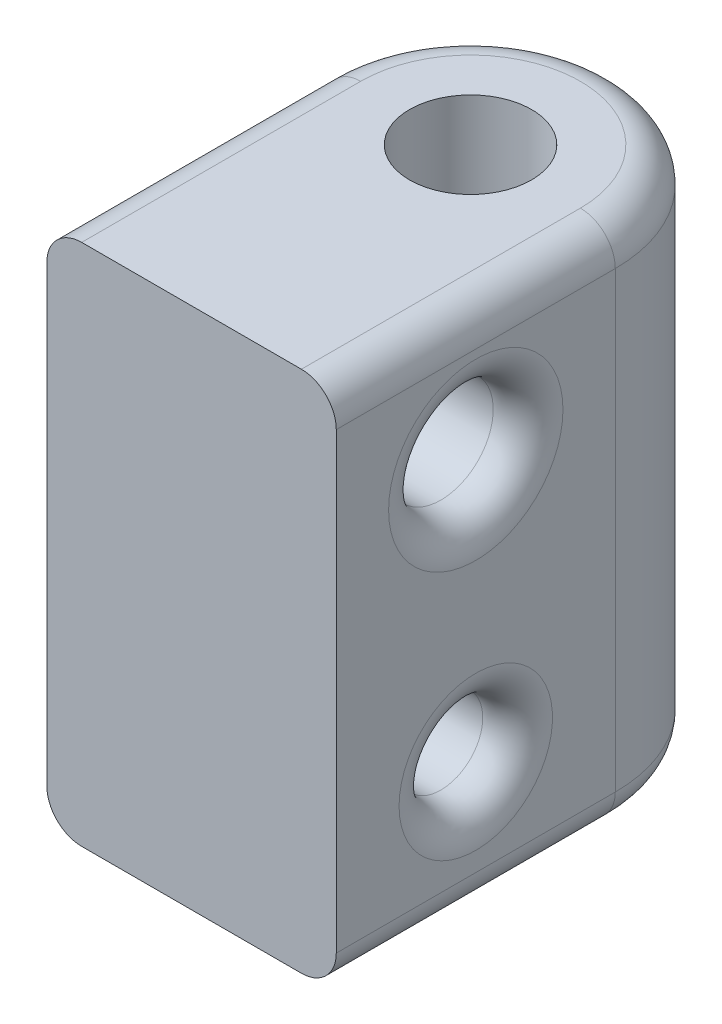
SolidWorks part; units mm, degrees
ref_plane "Front Plane" through (0, 0, 0) normal (0, 0, 1) x (1, 0, 0)
ref_plane "Top Plane" through (0, 0, 0) normal (0, 1, 0) x (1, 0, 0)
ref_plane "Right Plane" through (0, 0, 0) normal (1, 0, 0) x (0, 0, -1)
sketch "Sketch2" plane through (0, 0, 0) normal (0, 1, 0) x (1, 0, 0)
  line L0 (-4.15, 0) -> (-4.15, -8)
  line L1 (-4.15, -8) -> (4.15, -8)
  line L2 (4.15, -8) -> (4.15, 0)
  line L3 (0, 0) -> (0, -8) construction
  circle A0 centre (0, 0) radius 1.75
  arc A1 (-4.15, 0) -> (4.15, 0) centre (0, 0) cw
  dimension "D1" = 3.5
  dimension "D2" = 2.4
  dimension "D3" = 8
extrude "Boss-Extrude1" add sketch "Sketch2" along normal mid plane 15
sketch "Sketch3" plane through (-4.15, 0, 0) normal (-1, 0, 0) x (0, 0, 1)
  line L0 (4, 3.75) -> (4, -3.75) construction
  line L1 (8, 7.5) -> (8, -7.5) construction
  circle A0 centre (4, -3.75) radius 1.2
  circle A1 centre (4, 3.75) radius 1.5
  point P6 (4, 0)
  point P8 (5, 4.0399)
  dimension "D1" = 2.4
  dimension "D2" = 3
  dimension "D3" = 4
  dimension "D4" = 7.5
extrude "Cut-Extrude1" cut sketch "Sketch3" against normal through all both
fillet "Fillet1" radius 1 4 edges at (-4.15, -3.75, 5.2) (4.15, -3.75, 5.2) (-4.15, 3.75, 5.5) (4.15, 3.75, 5.5)
fillet "Fillet2" radius 1 6 edges at (4.15, 7.5, 4) (-4.15, 7.5, 4) (4.15, -7.5, 4) (-4.15, -7.5, 4) (0, 7.5, -4.15) (0, -7.5, -4.15)
